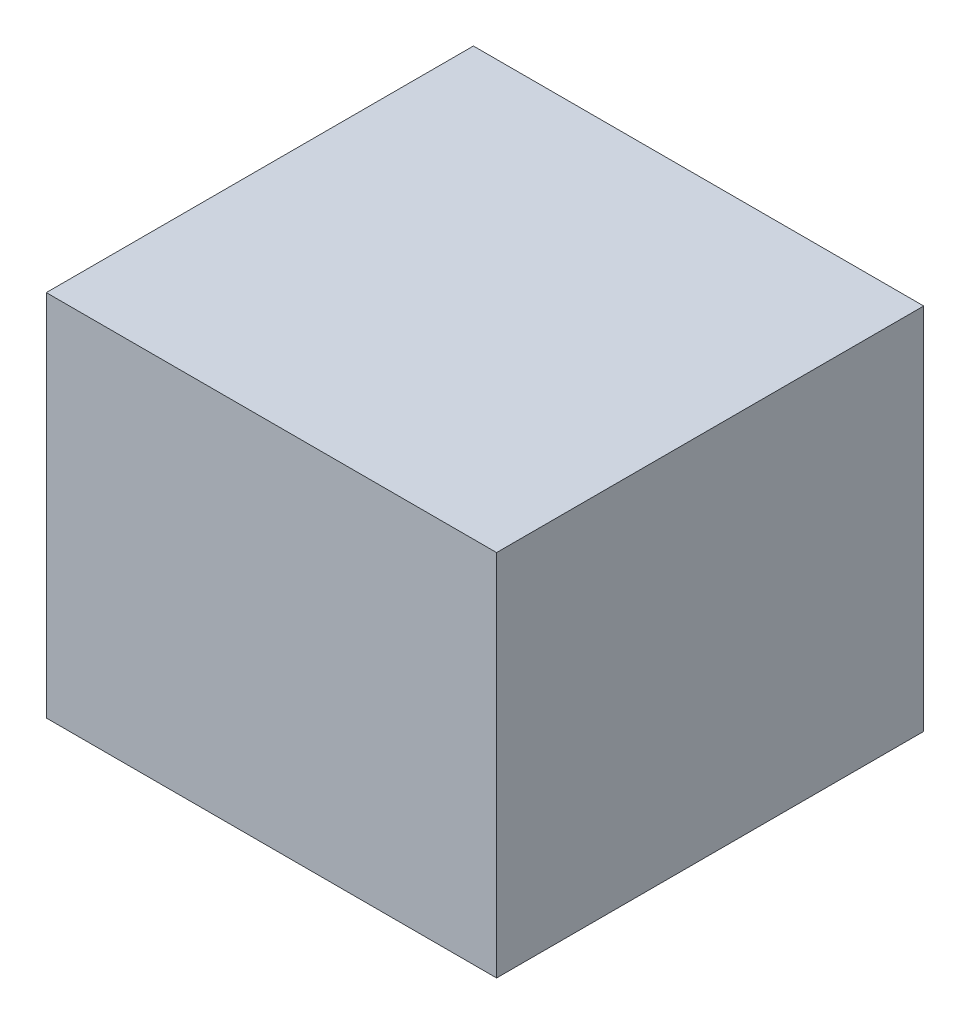
SolidWorks part; units mm, degrees
ref_plane "Front Plane" through (0, 0, 0) normal (0, 0, 1) x (1, 0, 0)
ref_plane "Top Plane" through (0, 0, 0) normal (0, 1, 0) x (1, 0, 0)
ref_plane "Right Plane" through (0, 0, 0) normal (1, 0, 0) x (0, 0, -1)
sketch "Sketch1" plane through (0, 0, 0) normal (0, 0, 1) x (1, 0, 0)
  line L1 (-8.25, -6.75) -> (8.25, -6.75)
  line L2 (-8.25, -6.75) -> (-8.25, 6.75)
  line L3 (-8.25, 6.75) -> (8.25, 6.75)
  line L4 (8.25, -6.75) -> (8.25, 6.75)
  line L5 (-8.25, -6.75) -> (8.25, 6.75) construction
  line L6 (-8.25, 6.75) -> (8.25, -6.75) construction
  point P0 (0, 0)
  dimension "D1" = 16.5
  dimension "D2" = 13.5
extrude "Boss-Extrude1" add sketch "Sketch1" along normal blind 15.65
sketch "Sketch2" plane through (0, 0, 0) normal (0, 0, 1) x (1, 0, 0)
  line L0 (-8.25, -6.75) -> (8.25, -6.75) construction
  line L1 (6.25, 4.85) -> (-6.25, 4.85)
  line L2 (6.25, 4.85) -> (6.25, -4.85)
  line L3 (6.25, -4.85) -> (-6.25, -4.85)
  line L4 (-6.25, 4.85) -> (-6.25, -4.85)
  line L5 (6.25, 4.85) -> (-6.25, -4.85) construction
  line L6 (6.25, -4.85) -> (-6.25, 4.85) construction
  line L7 (-8.25, 6.75) -> (-8.25, -6.75) construction
  line L8 (-6.25, 3.15) -> (6.25, 3.15)
  line L9 (8.25, 6.75) -> (-8.25, 6.75) construction
  line L10 (0, 0) -> (0, 6.75) construction
  line L12 (-3.2, -1.9466) -> (3.2, -1.9466)
  line L13 (-3.2, -1.9466) -> (-3.2, 5.75)
  line L14 (-3.2, 5.75) -> (3.2, 5.75)
  line L15 (3.2, -1.9466) -> (3.2, 5.75)
  line L16 (-3.2, -1.9466) -> (3.2, 5.75) construction
  line L17 (-3.2, 5.75) -> (3.2, -1.9466) construction
  point P0 (0, 0)
  point P16 (0, 1.9017)
  dimension "D1" = 1.9
  dimension "D2" = 2
  dimension "D3" = 3.6
  dimension "D4" = 1
  dimension "D5" = 6.4
extrude "Cut-Extrude1" cut sketch "Sketch2" along normal blind 10 contours L15 L12 L13 L8 L4 L3 L2 | L12 L15 L8 L13 | L8 L15 L1 L13 | L1 L15 L14 L13
